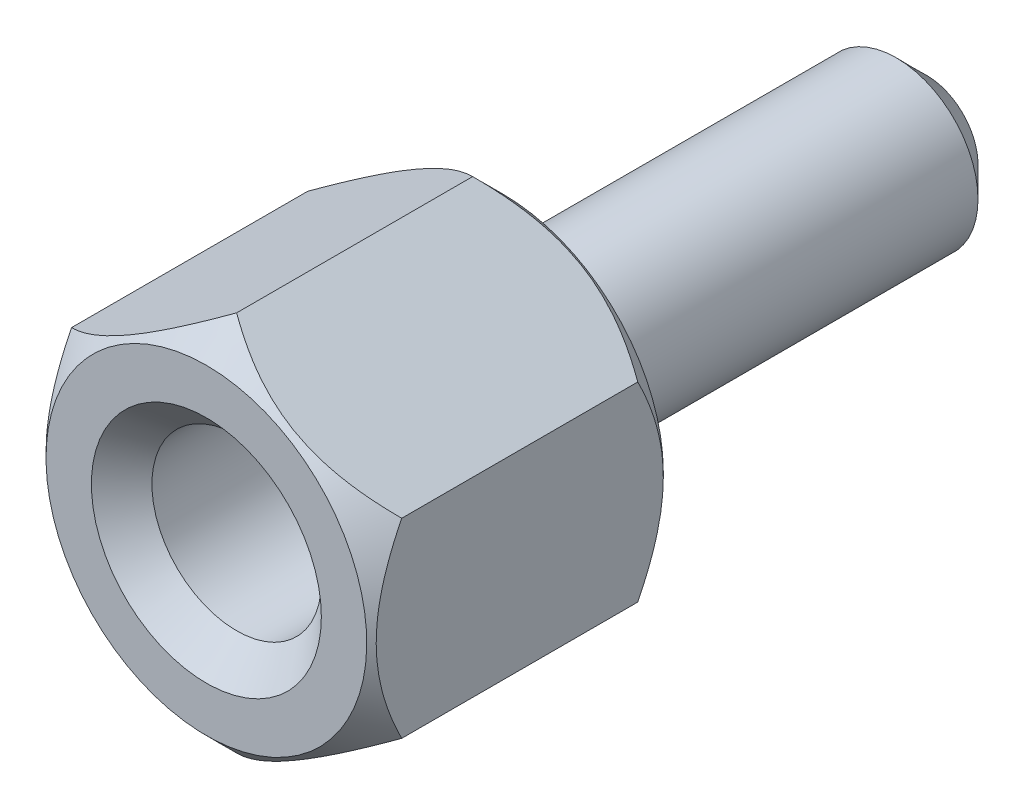
SolidWorks part; units mm, degrees
material "1023 Chapa de aço carbono (SS)"
ref_plane "Plano frontal" through (0, 0, 0) normal (0, 0, 1) x (1, 0, 0)
ref_plane "Plano superior" through (0, 0, 0) normal (0, 1, 0) x (1, 0, 0)
ref_plane "Plano direito" through (0, 0, 0) normal (1, 0, 0) x (0, 0, -1)
sketch "Esboço1" plane through (0, 0, 0) normal (0, 0, 1) x (1, 0, 0)
  line L0 (0, 3.15) -> (0, 0) construction
  line L1 (-2.728, 1.575) -> (-2.728, -1.575)
  line L2 (-2.728, -1.575) -> (0, -3.15)
  line L3 (0, -3.15) -> (2.728, -1.575)
  line L4 (2.728, -1.575) -> (2.728, 1.575)
  line L5 (2.728, 1.575) -> (0, 3.15)
  line L6 (0, 3.15) -> (-2.728, 1.575)
  circle A0 centre (0, 0) radius 3.15 construction
  dimension "D1" = 6.3
extrude "Ressalto-extrusão1" add sketch "Esboço1" along normal blind 4.9
sketch "Esboço8" plane through (0, 0, 0) normal (1, 0, 0) x (0, 0, -1)
  line L0 (-4.4, 3.15) -> (-4.9, 2.65)
  line L1 (-4.9, 3.15) -> (0, 3.15) construction
  line L2 (-4.9, 3.15) -> (-4.9, 1.575) construction
  line L3 (-4.9, 3.15) -> (-4.4, 3.15)
  line L4 (-4.9, 3.15) -> (-4.9, 2.65)
  line L5 (0, 3.15) -> (-0.5, 3.15)
  line L6 (-0.5, 3.15) -> (0, 2.65)
  line L7 (0, 3.15) -> (0, 1.575) construction
  line L8 (0, 2.65) -> (0, 3.15)
  line L9 (0, 0) -> (-4.9, 0) construction
  line L10 (-4.9, 1.575) -> (-4.9, -1.575) construction
  dimension "D1" = 0.5
  dimension "D2" = 0.5
  dimension "D3" = 0.5
  dimension "D4" = 0.5
revolve "Corte-Revolução1" cut sketch "Esboço8" angle 360 about L9
sketch "Esboço10" plane through (0, 0, 0) normal (0, 0, -1) x (-1, 0, 0)
  circle A0 centre (0, 0) radius 1.35
  dimension "D1" = 2.7
extrude "Ressalto-extrusão2" add sketch "Esboço10" along normal blind 7
cosmetic thread "Representação de rosca2" parameters "D2"=1.7
sketch "Esboço11" plane through (0, 0, 4.9) normal (0, 0, 1) x (1, 0, 0)
  circle A0 centre (0, 0) radius 1.4
  dimension "D1" = 2.8
extrude "Corte-extrusão1" cut sketch "Esboço11" against normal blind 3.5
cosmetic thread "Representação de rosca3" parameters "D2"=3
chamfer "Chanfro1" distance 0.5 angle 45 1 edges at (1.4, 0, 4.9)
chamfer "Chanfro2" distance 0.5 angle 45 1 edges at (-1.35, 0, -7)
